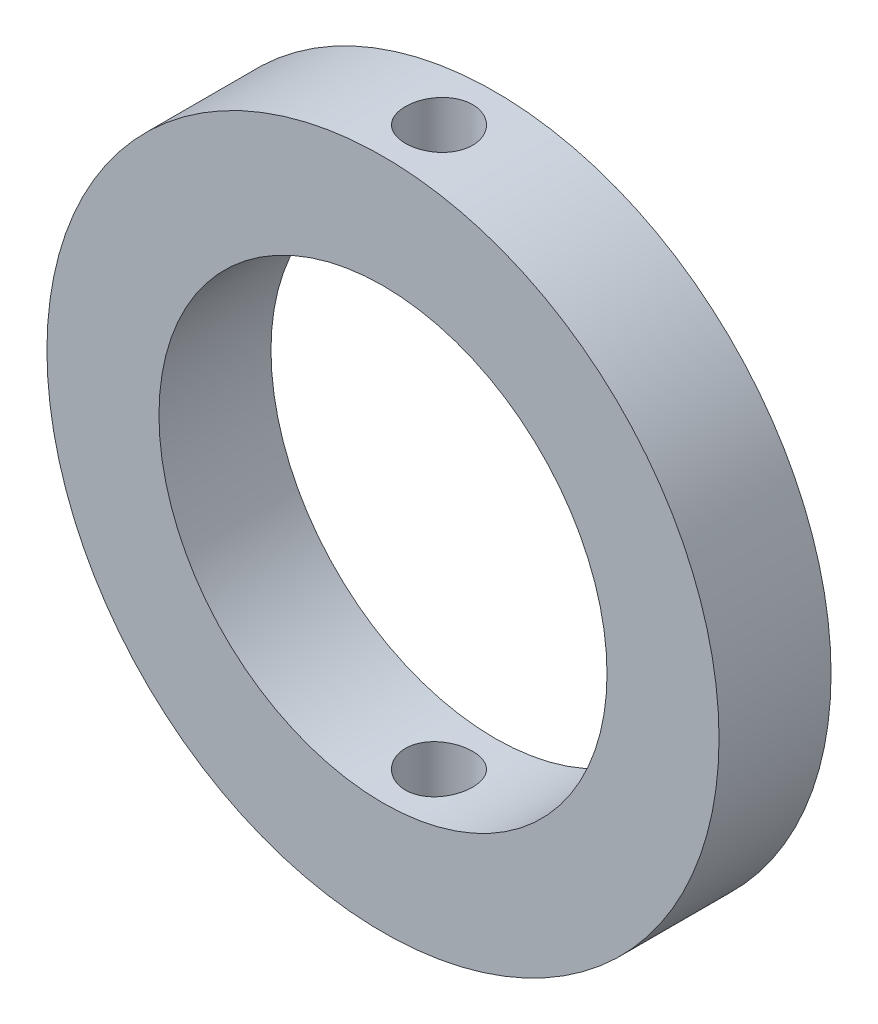
SolidWorks part; units mm, degrees
ref_plane "Front Plane" through (0, 0, 0) normal (0, 0, 1) x (1, 0, 0)
ref_plane "Top Plane" through (0, 0, 0) normal (0, 1, 0) x (1, 0, 0)
ref_plane "Right Plane" through (0, 0, 0) normal (1, 0, 0) x (0, 0, -1)
sketch "Sketch1" plane through (0, 0, 0) normal (0, 0, 1) x (1, 0, 0)
  circle A0 centre (0, 0) radius 20
  circle A1 centre (0, 0) radius 30
  dimension "D1" = 40
  dimension "D2" = 60
extrude "Boss-Extrude1" add sketch "Sketch1" along normal blind 10
sketch "Sketch2" plane through (0, 0, 0) normal (0, 1, 0) x (1, 0, 0)
  line L0 (-30, -5) -> (30, -5) construction
  line L1 (-30, 0) -> (-30, -10) construction
  line L2 (30, -10) -> (30, 0) construction
  circle A0 centre (0, -5) radius 3
extrude "Cut-Extrude1" cut sketch "Sketch2" against normal through all both and the other way through all
